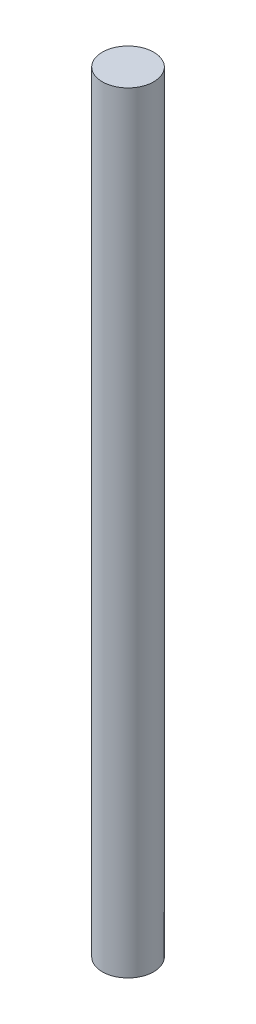
SolidWorks part; units mm, degrees
ref_plane "Front Plane" through (0, 0, 0) normal (0, 0, 1) x (1, 0, 0)
ref_plane "Top Plane" through (0, 0, 0) normal (0, 1, 0) x (1, 0, 0)
ref_plane "Right Plane" through (0, 0, 0) normal (1, 0, 0) x (0, 0, -1)
sketch "Sketch1" plane through (0, 0, 0) normal (0, 1, 0) x (1, 0, 0)
  circle A0 centre (0, 0) radius 6
  dimension "D1" = 12
extrude "Boss-Extrude1" add sketch "Sketch1" along normal blind 180
